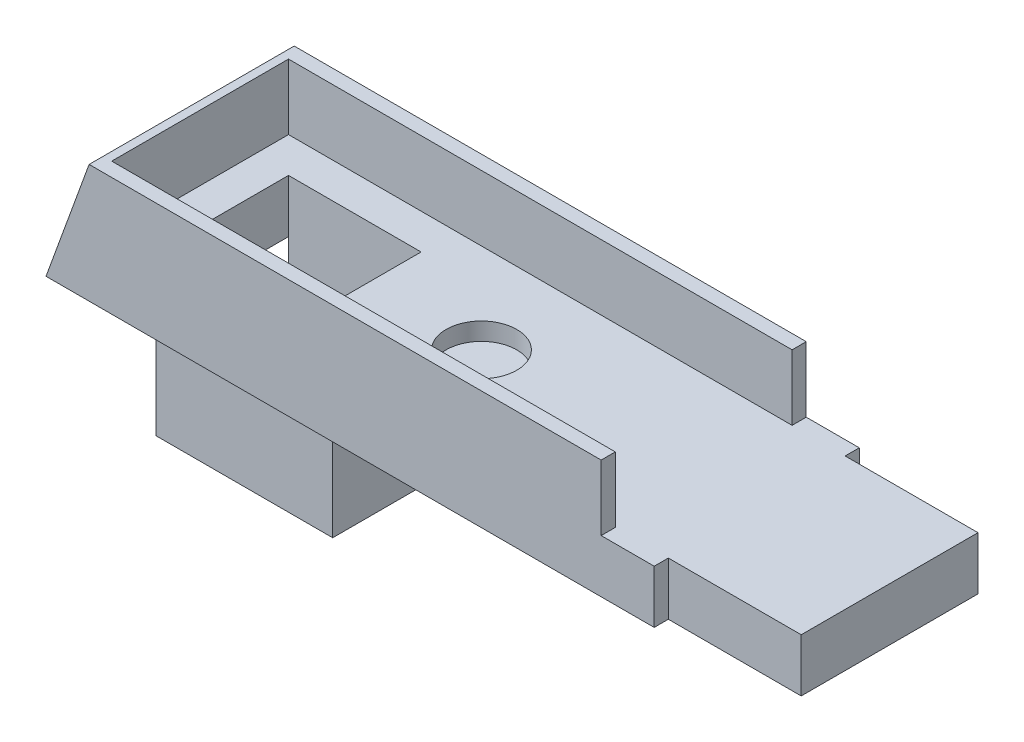
SolidWorks part; units mm, degrees
ref_plane "前视基准面" through (0, 0, 0) normal (0, 0, 1) x (1, 0, 0)
ref_plane "上视基准面" through (0, 0, 0) normal (0, 1, 0) x (1, 0, 0)
ref_plane "右视基准面" through (0, 0, 0) normal (1, 0, 0) x (0, 0, -1)
sketch "草图1" plane through (0, 0, 0) normal (0, 1, 0) x (1, 0, 0)
  line L0 (-13.0089, -6.3971) -> (-13.0089, -12.3971)
  line L1 (-14.0089, -4.3971) -> (-4.0242, -4.3971) construction
  line L2 (-14.0089, -4.3971) -> (-14.0089, -14.3971) construction
  line L3 (-14.0089, -14.3971) -> (-4.0242, -14.3971) construction
  line L4 (23.9911, -4.3971) -> (23.9911, -14.3971)
  line L5 (-13.0089, -12.3971) -> (-5.5089, -12.3971)
  line L6 (-5.5089, -12.3971) -> (-5.5089, -6.3971)
  line L7 (-5.5089, -6.3971) -> (-13.0089, -6.3971)
  line L9 (-53.0418, -9.3971) -> (30.158, -9.3971) construction
  line L13 (3.9758, -4.3971) -> (23.9911, -4.3971) construction
  line L17 (3.9758, -14.3971) -> (23.9911, -14.3971) construction
  line L18 (-4.0242, -3.5971) -> (-16.0089, -3.5971)
  line L19 (-16.0089, -3.5971) -> (-16.0089, -15.1971)
  line L20 (-16.0089, -15.1971) -> (-4.0242, -15.1971)
  line L21 (2.9758, -3.5971) -> (16.4758, -3.5971)
  line L22 (16.4758, -3.5971) -> (16.4758, -4.3971)
  line L23 (16.4758, -15.1971) -> (16.4758, -14.3971)
  line L24 (2.9758, -15.1971) -> (16.4758, -15.1971)
  line L25 (16.4758, -4.3971) -> (23.9911, -4.3971)
  line L26 (23.9911, -14.3971) -> (16.4758, -14.3971)
  line L27 (-4.0242, -15.1971) -> (2.9758, -15.1971)
  line L28 (-4.0242, -3.5971) -> (2.9758, -3.5971)
  point P11 (-15.2327, -3.3971)
  point P12 (23.9911, -9.3971)
  point P14 (0, 0)
  point P17 (-5.5089, -11.3971)
  point P18 (-5.5089, -12.3971)
  point P30 (-5.5089, -11.3971)
  point P31 (-5.5089, -12.3203)
  dimension "D1" = 38
  dimension "D2" = 10
  dimension "D3" = 6
  dimension "D4" = 2
  dimension "D5" = 7.5
  dimension "D7" = 1
  dimension "D10" = 0.8
  dimension "D11" = 2
  dimension "D12" = 0.8
  dimension "D14" = 12.5
extrude "凸台-拉伸1" add sketch "草图1" along normal blind 3
sketch "草图2" plane through (0, 0, 0) normal (0, -1, 0) x (1, 0, 0)
  line L12 (-13.0089, 12.3971) -> (-13.0089, 13.8971)
  line L13 (-13.0089, 13.8971) -> (-3.0089, 13.8971)
  line L14 (-3.0089, 13.8971) -> (-3.0089, 4.8971)
  line L15 (-3.0089, 4.8971) -> (-13.0089, 4.8971)
  line L16 (-13.0089, 4.8971) -> (-13.0089, 6.3971)
  line L17 (-13.0089, 6.3971) -> (-13.0089, 12.3971) construction
  line L18 (-5.5089, 9.3971) -> (-6.8487, 9.3971) construction
  line L19 (-13.0089, 12.3971) -> (-5.5089, 12.3971)
  line L21 (-13.0089, 6.3971) -> (-5.5089, 6.3971)
  line L22 (-5.5089, 12.3971) -> (-5.5089, 6.3971)
  dimension "D1" = 1.5
  dimension "D2" = 2.5
extrude "凸台-拉伸2" add sketch "草图2" along normal blind 6
sketch "草图3" plane through (0, 3, 0) normal (0, 1, 0) x (1, 0, 0)
  line L0 (-14.0089, -9.4845) -> (-14.0089, -12.8636) construction
  line L1 (-17.6334, -9.4845) -> (28.8033, -9.4845) construction
  line L3 (-13.0089, -6.3971) -> (-13.0089, -12.3971) construction
  circle A0 centre (0.9911, -9.4845) radius 2
  point P12 (-14.0089, -12.2131)
  dimension "D1" = 4
  dimension "D2" = 15
  dimension "D3" = 1
extrude "切除-拉伸1" cut sketch "草图3" against normal blind 1
sketch "草图4" plane through (0, 3, 0) normal (0, 1, 0) x (1, 0, 0)
  line L0 (-16.0089, -3.5971) -> (13.4758, -3.5971)
  line L1 (16.4758, -3.5971) -> (16.4758, -4.3971) construction
  line L2 (13.4758, -4.3971) -> (-15.0089, -4.3971)
  line L3 (-16.0089, -3.5971) -> (-16.0089, -15.1971)
  line L4 (-16.0089, -15.1971) -> (13.4758, -15.1971)
  line L5 (16.4758, -15.1971) -> (16.4758, -14.3971) construction
  line L6 (13.4758, -14.3971) -> (-15.0089, -14.3971)
  line L7 (-15.0089, -14.3971) -> (-15.0089, -4.3971)
  line L8 (13.4758, -14.3971) -> (13.4758, -15.1971)
  line L9 (13.4758, -15.1971) -> (16.4758, -15.1971) construction
  line L10 (16.4758, -14.3971) -> (13.4758, -14.3971) construction
  line L11 (13.4758, -3.5971) -> (13.4758, -4.3971)
  line L12 (13.4758, -3.5971) -> (16.4758, -3.5971) construction
  line L13 (16.4758, -4.3971) -> (13.4758, -4.3971) construction
  dimension "D1" = 1
  dimension "D2" = 3
extrude "凸台-拉伸3" add sketch "草图4" along normal blind 3.7
sketch "草图5" plane through (0, 6.7, 0) normal (0, 1, 0) x (1, 0, 0)
  line L0 (-16.0089, -3.5971) -> (-16.0089, -15.1971)
  line L1 (-16.0089, -15.1971) -> (-5.5089, -15.1971)
  line L2 (-16.0089, -15.1971) -> (13.4758, -15.1971) construction
  line L3 (-16.0089, -3.5971) -> (-5.5089, -3.5971)
  line L4 (13.4758, -3.5971) -> (-16.0089, -3.5971) construction
  line L5 (-5.5089, -3.5971) -> (-5.5089, -10.0171)
  line L6 (-8.2089, -10.0171) -> (-8.2089, -12.5171)
  line L7 (-8.2089, -12.5171) -> (-5.5089, -12.5171)
  line L9 (-5.5089, -10.0171) -> (-8.2089, -10.0171)
  line L10 (-5.5089, -12.5171) -> (-5.5089, -15.1971)
  dimension "D1" = 7.8
  dimension "D2" = 2.68
  dimension "D3" = 2.5
  dimension "D4" = 2.7
sketch "草图6" plane through (0, 3, 0) normal (0, 1, 0) x (1, 0, 0)
  line L0 (-16.0089, -3.5971) -> (-16.0089, -15.1971) construction
  line L2 (-17.6881, -9.3971) -> (25.119, -9.3971) construction
  point P0 (-16.0089, -9.3971)
  point P1 (-16.0089, -9.3971)
sketch "草图7" plane through (0, 0, 15.1971) normal (0, 0, 1) x (1, 0, 0)
  line L0 (-16.0089, 0) -> (-16.0089, 6.7)
  line L1 (-16.0089, 6.7) -> (-18.4475, 0)
  line L3 (-18.4475, 0) -> (-16.0089, 0)
  dimension "D1" = 20
extrude "凸台-拉伸4" add sketch "草图7" against normal up to surface (11.6 mm away) up to face at (4.6476, 3.2333, 3.5971)
sketch "草图8" plane through (0, 0, 15.1971) normal (0, 0, 1) x (1, 0, 0)
  line L0 (-16.0089, 6.7) -> (-18.4475, 0)
  line L1 (-18.4475, 0) -> (-17.9261, 0)
  line L2 (-18.4475, 0) -> (16.4758, 0) construction
  line L3 (-17.9261, 0) -> (-15.4875, 6.7)
  line L4 (-16.0089, 6.7) -> (-5.5089, 6.7) construction
  line L5 (-15.4875, 6.7) -> (-16.0089, 6.7)
  dimension "D1" = 0.49
extrude "切除-拉伸2" cut sketch "草图8" against normal blind 12
